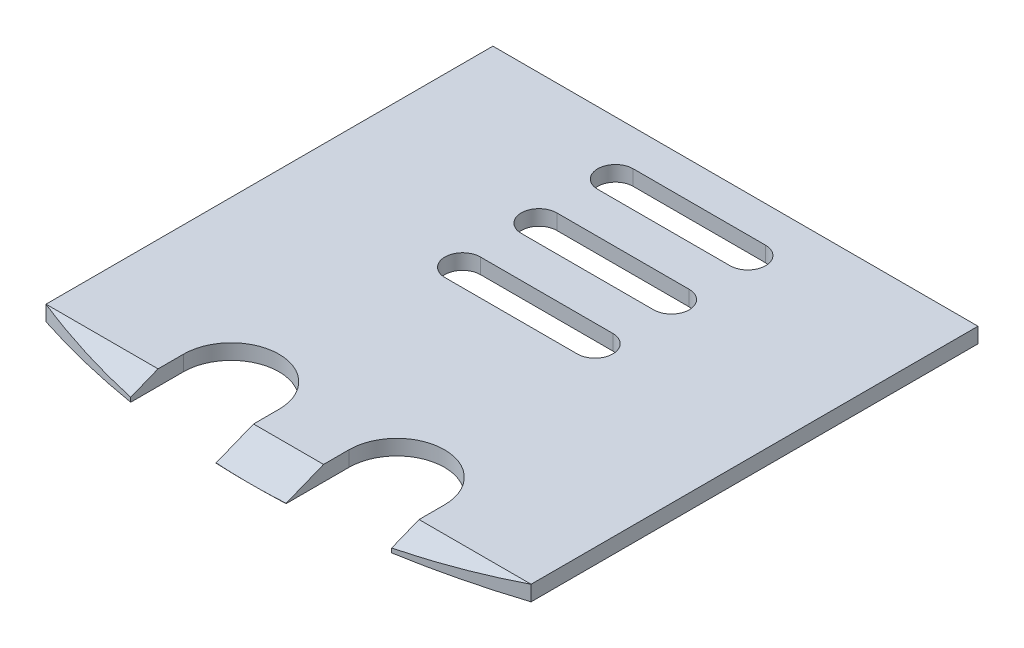
SolidWorks part; units mm, degrees
ref_plane "Front Plane" through (0, 0, 0) normal (0, 0, 1) x (1, 0, 0)
ref_plane "Top Plane" through (0, 0, 0) normal (0, 1, 0) x (1, 0, 0)
ref_plane "Right Plane" through (0, 0, 0) normal (1, 0, 0) x (0, 0, -1)
sketch "Sketch1" plane through (0, 0, 0) normal (0, 1, 0) x (1, 0, 0)
  line L0 (-5.125, -7.025) -> (-5.125, -9.0983)
  line L1 (-9.525, 9.525) -> (9.525, 9.525)
  line L2 (-9.525, 9.525) -> (-9.525, -8.025)
  line L4 (9.525, 9.525) -> (9.525, -8.025)
  line L5 (-9.525, 9.525) -> (8.3726, -8.3726) construction
  line L6 (-8.3726, -8.3726) -> (9.525, 9.525) construction
  line L7 (-1.375, -7.025) -> (-1.375, -9.4945)
  line L8 (1.375, -7.025) -> (1.375, -9.4945)
  line L9 (5.125, -7.025) -> (5.125, -9.0983)
  arc A0 (-1.375, -7.025) -> (-5.125, -7.025) centre (-3.25, -7.025) ccw
  arc A1 (5.125, -7.025) -> (1.375, -7.025) centre (3.25, -7.025) ccw
  arc A2 (-9.525, -8.025) -> (-5.125, -9.0983) centre (0, 21.4669) ccw
  arc A3 (5.125, -9.0983) -> (9.525, -8.025) centre (0, 21.4669) ccw
  arc A4 (-1.375, -9.4945) -> (1.375, -9.4945) centre (0, 21.4669) ccw
  point P0 (0, 0)
  dimension "D5" = 3.75
  dimension "D6" = 3.75
  dimension "D2" = 19.05
  dimension "D3" = 6.5
  dimension "D7" = 6.275
extrude "Boss-Extrude1" add sketch "Sketch1" along normal blind 0.6
sketch "Sketch2" plane through (0, 0, 0) normal (1, 0, 0) x (0, 0, -1)
  line L0 (-9.525, 0) -> (-8.025, 0.6)
  line L1 (-8.025, 0.6) -> (-9.525, 0.6)
  line L2 (-9.525, 0.6) -> (-9.525, 0)
extrude "Cut-Extrude1" cut sketch "Sketch2" against normal through all both and the other way through all
sketch "Sketch3" plane through (0, 0.6, 0) normal (0, 1, 0) x (1, 0, 0)
  line L0 (2.5993, 7.4117) -> (-2.5993, 7.4117) construction
  line L1 (2.5993, 6.7136) -> (-2.5993, 6.7136)
  line L2 (2.5993, 8.1098) -> (-2.5993, 8.1098)
  line L3 (2.5993, 4.4117) -> (-2.5993, 4.4117) construction
  line L4 (2.5993, 3.7136) -> (-2.5993, 3.7136)
  line L5 (2.5993, 5.1098) -> (-2.5993, 5.1098)
  line L6 (2.5993, 1.4117) -> (-2.5993, 1.4117) construction
  line L7 (2.5993, 0.7136) -> (-2.5993, 0.7136)
  line L8 (2.5993, 2.1098) -> (-2.5993, 2.1098)
  arc A0 (2.5993, 6.7136) -> (2.5993, 8.1098) centre (2.5993, 7.4117) ccw
  arc A1 (-2.5993, 8.1098) -> (-2.5993, 6.7136) centre (-2.5993, 7.4117) ccw
  arc A2 (2.5993, 3.7136) -> (2.5993, 5.1098) centre (2.5993, 4.4117) ccw
  arc A3 (-2.5993, 5.1098) -> (-2.5993, 3.7136) centre (-2.5993, 4.4117) ccw
  arc A4 (2.5993, 0.7136) -> (2.5993, 2.1098) centre (2.5993, 1.4117) ccw
  arc A5 (-2.5993, 2.1098) -> (-2.5993, 0.7136) centre (-2.5993, 1.4117) ccw
  point P2 (0, 7.4117)
  point P11 (0, 4.4117)
  point P18 (0, 1.4117)
  dimension "D1" = 3
extrude "Cut-Extrude2" cut sketch "Sketch3" against normal up to next
